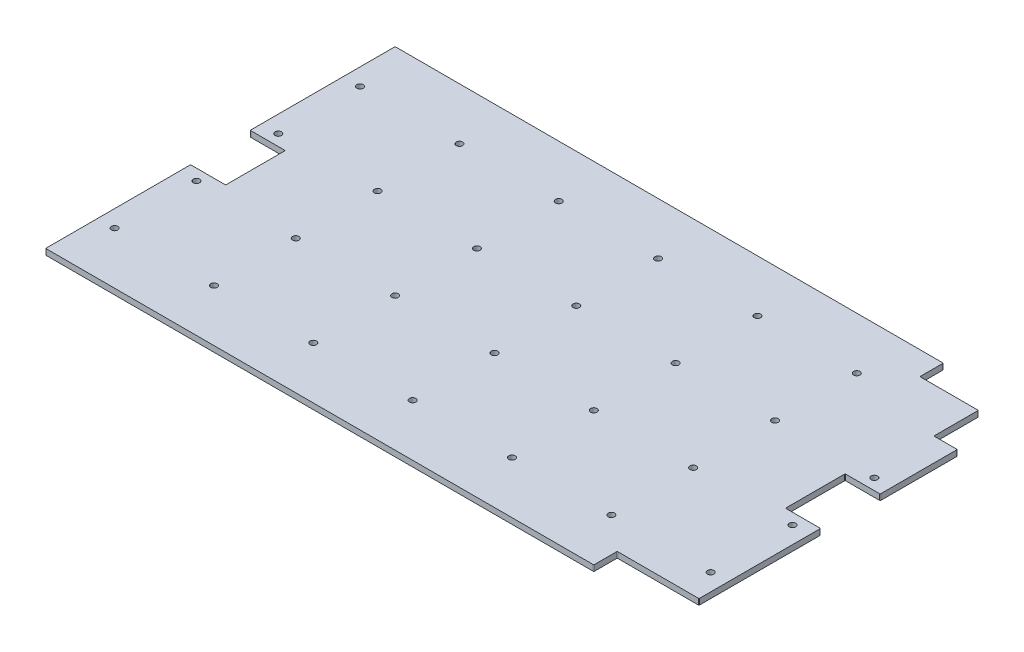
SolidWorks part; units mm, degrees
ref_plane "Front Plane" through (0, 0, 0) normal (0, 0, 1) x (1, 0, 0)
ref_plane "Top Plane" through (0, 0, 0) normal (0, 1, 0) x (1, 0, 0)
ref_plane "Right Plane" through (0, 0, 0) normal (1, 0, 0) x (0, 0, -1)
sketch "Sketch1" plane through (0, 0, 0) normal (0, 1, 0) x (1, 0, 0)
  line L1 (269.5, -149.5) -> (-269.5, -149.5)
  line L2 (269.5, -149.5) -> (269.5, 149.5)
  line L3 (269.5, 149.5) -> (-269.5, 149.5)
  line L4 (-269.5, -149.5) -> (-269.5, 149.5)
  line L5 (269.5, -149.5) -> (-269.5, 149.5) construction
  line L6 (269.5, 149.5) -> (-269.5, -149.5) construction
  point P0 (0, 0)
  dimension "D1" = 539
  dimension "D2" = 299
extrude "Boss-Extrude1" add sketch "Sketch1" along normal blind 5
sketch "Sketch5" plane through (0, 5, 0) normal (0, 1, 0) x (1, 0, 0)
  line L0 (269.5, 149.5) -> (199.5, 149.5)
  line L1 (269.5, 149.5) -> (-269.5, 149.5) construction
  line L2 (199.5, 149.5) -> (199.5, 129.5)
  line L3 (199.5, 129.5) -> (249.5, 129.5)
  line L4 (249.5, 129.5) -> (249.5, 91.5)
  line L5 (249.5, 91.5) -> (269.5, 91.5)
  line L6 (269.5, -149.5) -> (269.5, 149.5) construction
  line L7 (269.5, 91.5) -> (269.5, 149.5)
  line L8 (269.5, -149.5) -> (199.5, -149.5)
  line L9 (-269.5, -149.5) -> (269.5, -149.5) construction
  line L10 (199.5, -149.5) -> (199.5, -129.5)
  line L11 (199.5, -129.5) -> (269.5, -129.5)
  line L12 (269.5, -129.5) -> (269.5, -149.5)
  dimension "D1" = 20
  dimension "D2" = 20
  dimension "D3" = 20
  dimension "D4" = 70
  dimension "D5" = 70
  dimension "D6" = 58
extrude "Cut-Extrude2" cut sketch "Sketch5" against normal through all
sketch "Sketch2" plane through (0, 5, 0) normal (0, 1, 0) x (1, 0, 0)
  line L0 (0, 0) -> (-269.5, 0) construction
  line L1 (-269.5, 149.5) -> (-269.5, -149.5) construction
  line L3 (-239.5, -25.5) -> (-269.5, -25.5)
  line L4 (-239.5, -25.5) -> (-239.5, 25.5)
  line L5 (-239.5, 25.5) -> (-269.5, 25.5)
  line L6 (-269.5, -25.5) -> (-269.5, 25.5)
  line L7 (-239.5, -25.5) -> (-269.5, 25.5) construction
  line L8 (-239.5, 25.5) -> (-269.5, -25.5) construction
  point P5 (-254.5, 0)
  dimension "D1" = 30
  dimension "D2" = 51
extrude "Cut-Extrude1" cut sketch "Sketch2" against normal through all
mirror "Mirror1" about plane through (0, 0, 0) normal (1, 0, 0) of "Cut-Extrude1"
sketch "Sketch3" plane through (0, 5, 0) normal (0, 1, 0) x (1, 0, 0)
  point P0 (-255, -105)
  dimension "D1" = 255
  dimension "D2" = 105
hole_wizard "Ø5.5 (5.5) Diameter Hole1" positions "3DSketch1" profile "Sketch4" hole size "Ø5.5" standard "ANSI Metric" end condition through all
sketch3d "3DSketch1"
  point P0 (-255, 5, 105)
sketch "Sketch4" plane through (-255, 5, 105) normal (1, 0, 0) x (0, 0, 1)
  line L0 (0, 0) -> (0, 5)
  line L1 (0, 5) -> (2.75, 5)
  line L2 (2.75, 5) -> (2.75, 0)
  line L5 (2.75, 0) -> (0, 0)
  line L11 (0, -6.35) -> (0, 107.95) construction
  dimension "Thru Hole Dia." = 5.5
  dimension "Thru Hole Depth" = 5
pattern_linear "LPattern1" count 7 spacing 85 along (1, 0, 0) count 4 spacing 70 along (0, 0, -1) skipping (6, 3) of "Ø5.5 (5.5) Diameter Hole1"
fillet "Fillet1" radius 0.5 18 edges at (239.5, 2.5, 25.5) (239.5, 2.5, -25.5) (269.5, 2.5, -25.5) (269.5, 2.5, -91.5) (249.5, 2.5, -91.5) (249.5, 2.5, -129.5) (199.5, 2.5, -129.5) (199.5, 2.5, -149.5) (-269.5, 2.5, -149.5) (-239.5, 2.5, -25.5) (-239.5, 2.5, 25.5) (-269.5, 2.5, 25.5) (-269.5, 2.5, 149.5) (199.5, 2.5, 149.5) (199.5, 2.5, 129.5) (269.5, 2.5, 129.5) (269.5, 2.5, 25.5) (-269.5, 2.5, -25.5)
